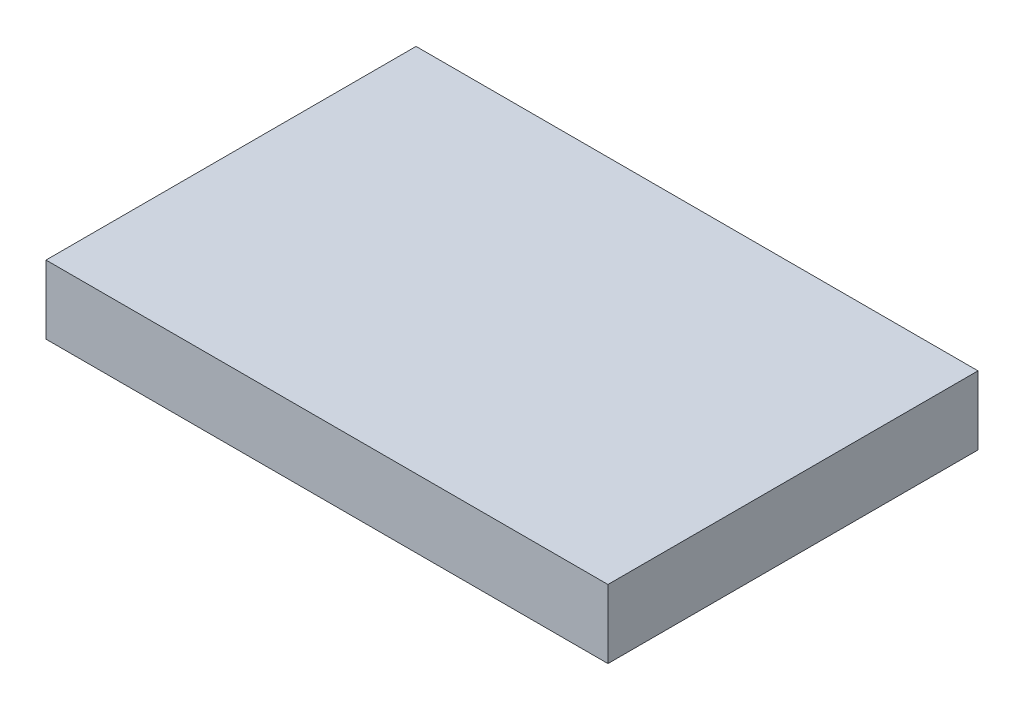
SolidWorks part; units mm, degrees
ref_plane "Front Plane" through (0, 0, 0) normal (0, 0, 1) x (1, 0, 0)
ref_plane "Top Plane" through (0, 0, 0) normal (0, 1, 0) x (1, 0, 0)
ref_plane "Right Plane" through (0, 0, 0) normal (1, 0, 0) x (0, 0, -1)
sketch "Sketch1" plane through (0, 0, 0) normal (0, 1, 0) x (1, 0, 0)
  line L1 (0, 0) -> (82, 0)
  line L2 (0, 0) -> (0, 54)
  line L3 (0, 54) -> (82, 54)
  line L4 (82, 0) -> (82, 54)
  dimension "D1" = 54
  dimension "D2" = 82
extrude "Boss-Extrude1" add sketch "Sketch1" along normal blind 10
